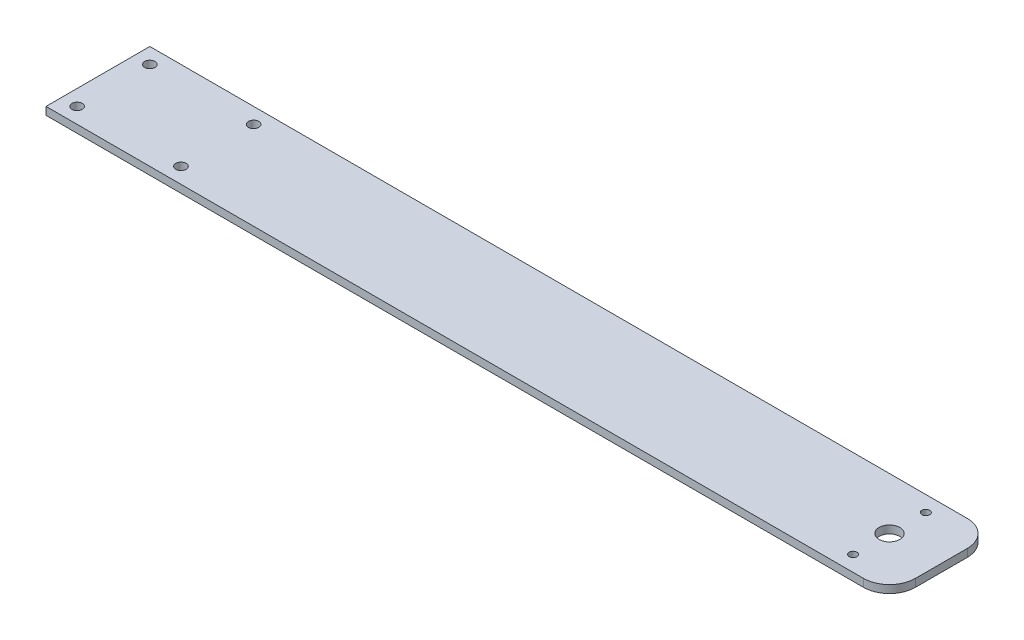
SolidWorks part; units mm, degrees
ref_plane "Front Plane" through (0, 0, 0) normal (0, 0, 1) x (1, 0, 0)
ref_plane "Top Plane" through (0, 0, 0) normal (0, 1, 0) x (1, 0, 0)
ref_plane "Right Plane" through (0, 0, 0) normal (1, 0, 0) x (0, 0, -1)
sketch "Sketch1" plane through (0, 0, 0) normal (0, 1, 0) x (1, 0, 0)
  line L0 (-162.5, 0) -> (162.5, 0) construction
  line L1 (-162.5, 20) -> (162.5, 20)
  line L2 (-162.5, 20) -> (-162.5, -20)
  line L3 (-162.5, -20) -> (162.5, -20)
  line L4 (162.5, 20) -> (162.5, -20)
  line L5 (-162.5, 20) -> (162.5, -20) construction
  line L6 (-162.5, -20) -> (162.5, 20) construction
  line L7 (0, 20) -> (0, -20) construction
  line L8 (-156.5, 14) -> (-116.5, 14) construction
  line L9 (-156.5, 14) -> (-156.5, -14) construction
  line L10 (-156.5, -14) -> (-116.5, -14) construction
  line L11 (-116.5, 14) -> (-116.5, -14) construction
  line L12 (-156.5, 14) -> (-116.5, -14) construction
  line L13 (-156.5, -14) -> (-116.5, 14) construction
  line L14 (142.5, 20) -> (142.5, -20) construction
  circle A0 centre (-156.5, 14) radius 2
  circle A1 centre (-116.5, 14) radius 2
  circle A2 centre (-116.5, -14) radius 2
  circle A3 centre (-156.5, -14) radius 2
  circle A8 centre (142.5, 0) radius 4
  circle A9 centre (142.5, 14) radius 1.5
  circle A10 centre (142.5, -14) radius 1.5
  point P0 (0, 0)
  point P8 (-136.5, 0)
  point P20 (0, 0)
  point P25 (142.5, 0)
  dimension "D6" = 4
  dimension "D7" = 4
  dimension "D8" = 4
  dimension "D9" = 4
  dimension "D10" = 8
  dimension "D11" = 20
  dimension "D12" = 3
  dimension "D13" = 3
  dimension "D14" = 6
  dimension "D15" = 6
  dimension "D1" = 325
  dimension "D2" = 40
  dimension "D3" = 40
  dimension "D4" = 28
  dimension "D5" = 6
extrude "Boss-Extrude1" add sketch "Sketch1" along normal blind 3
fillet "Fillet1" radius 10 2 edges at (162.5, 1.5, 20) (162.5, 1.5, -20)
